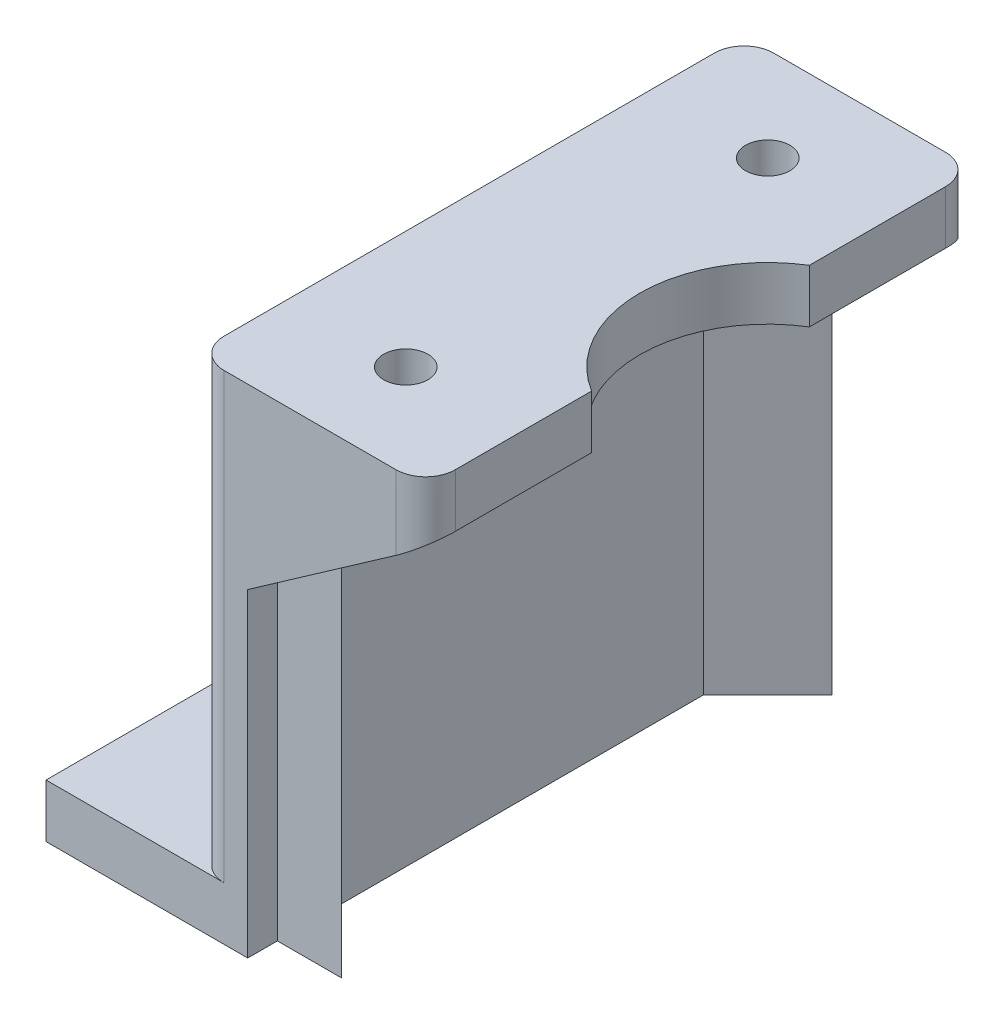
SolidWorks part; units mm, degrees
ref_plane "Front Plane" through (0, 0, 0) normal (0, 0, 1) x (1, 0, 0)
ref_plane "Top Plane" through (0, 0, 0) normal (0, 1, 0) x (1, 0, 0)
ref_plane "Right Plane" through (0, 0, 0) normal (1, 0, 0) x (0, 0, -1)
sketch "Sketch1" plane through (0, 0, 0) normal (0, 0, 1) x (1, 0, 0)
  line L0 (-41.9989, 1.778) -> (-46.5709, 1.778)
  line L1 (-46.5709, 6.35) -> (-46.5709, 44.3509)
  line L2 (-46.5709, 44.3509) -> (-26.7589, 44.3509)
  line L3 (-41.9989, 6.35) -> (-41.9989, 1.778)
  line L4 (-26.7589, 39.7789) -> (-41.9989, 39.7789)
  line L5 (-41.9989, 39.7789) -> (-41.9989, 6.35)
  line L7 (0, 6.35) -> (0, 0)
  line L8 (-26.7589, 44.3509) -> (-26.7589, 39.7789)
  line L9 (-46.5709, 1.778) -> (-59.2709, 1.778)
  line L11 (-46.5709, 6.35) -> (-59.2709, 6.35)
  line L12 (-59.2709, 1.778) -> (-59.2709, 6.35)
  dimension "D1" = 38.0009
  dimension "D2" = 15.24
  dimension "D3" = 4.572
  dimension "D4" = 4.572
  dimension "D5" = 41.9989
  dimension "D7" = 4.572
  dimension "D8" = 12.7
extrude "Boss-Extrude1" add sketch "Sketch1" along normal blind 47.0789 contours L12 L9 L0 L3 L5 L4 L8 L2 L1 L11
ref_plane "Plane1" through (0, 0, 23.5394) normal (0, 0, -1) x (-1, 0, 0)
sketch "Sketch2" plane through (0, 0, 47.0789) normal (0, 0, 1) x (1, 0, 0)
  line L0 (-26.7589, 39.7789) -> (-41.9989, 29.1109)
  line L1 (-41.9989, 39.7789) -> (-41.9989, 1.778) construction
  line L2 (-41.9989, 29.1109) -> (-41.9989, 39.7789)
  line L3 (-41.9989, 39.7789) -> (-26.7589, 39.7789)
extrude "Boss-Extrude2" add sketch "Sketch2" against normal blind 2.54
mirror "Mirror1" about plane through (0, 0, 23.5394) normal (0, 0, -1) of "Boss-Extrude2"
hole_wizard "#6 Clearance Hole1" positions "Sketch3" profile "Sketch4" hole size "#6" standard "ANSI Inch" end condition through all
sketch "Sketch3" plane through (0, 44.3509, 0) normal (0, 1, 0) x (1, 0, 0)
  line L0 (-36.4998, -8.0391) -> (-36.4998, -39.0398)
  line L5 (-46.5709, 0) -> (-46.5709, -47.0789)
  point P0 (-36.4998, -8.0391)
  point P2 (-36.4998, -39.0398)
  point P21 (-36.4998, -23.5394)
  point P22 (-46.5709, -23.5394)
  dimension "D1" = 31.0007
  dimension "D2" = 0
  dimension "D3" = 10.0711
sketch "Sketch4" plane through (-36.4998, 44.3509, 8.0391) normal (1, 0, 0) x (0, 0, 1)
  line L0 (0, 0) -> (0, 42.5729)
  line L1 (0, 42.5729) -> (1.8986, 42.5729)
  line L2 (1.8986, 42.5729) -> (1.8986, 0)
  line L5 (1.8986, 0) -> (0, 0)
  line L11 (0, -6.35) -> (0, 107.95) construction
  dimension "Thru Hole Dia." = 3.7973
  dimension "Thru Hole Depth" = 42.5729
sketch "Sketch5" plane through (0, 44.3509, 0) normal (0, 1, 0) x (1, 0, 0)
  line L0 (-26.7589, -23.5394) -> (-21.0007, -23.5394)
  line L1 (-26.7589, -47.0789) -> (-26.7589, 0) construction
  circle A0 centre (-21.0007, -23.5394) radius 10.9601
  line M7 (-26.7589, -47.0789) -> (-26.7589, 0)
  dimension "D2" = 21.9202
  dimension "D1" = 5.7582
extrude "Cut-Extrude1" cut sketch "Sketch5" against normal through all contours A0 M7
fillet "Fillet1" radius 2.54 4 edges at (-46.5709, 25.3505, 0) (-46.5709, 25.3505, 47.0789) (-26.7589, 42.0649, 47.0789) (-26.7589, 42.0649, 0)
hole_wizard "#6 Clearance Hole2" positions "Sketch6" profile "Sketch7" hole size "#6" standard "ANSI Inch" end condition through all
sketch "Sketch6" plane through (0, 6.35, 0) normal (0, 1, 0) x (1, 0, 0)
  line L0 (-52.9209, -10.8395) -> (-52.9209, -36.2394)
  line L2 (-59.2709, -47.0789) -> (-59.2709, 0) construction
  line L3 (-59.2709, 0) -> (-59.2709, -47.0789)
  point P0 (-52.9209, -10.8395)
  point P2 (-52.9209, -36.2394)
  point P16 (-59.2709, -23.5394)
  point P17 (-52.9209, -23.5394)
  dimension "D1" = 6.35
  dimension "D2" = 25.4
  dimension "D3" = 0
sketch "Sketch7" plane through (-52.9209, 6.35, 10.8395) normal (1, 0, 0) x (0, 0, 1)
  line L0 (0, 0) -> (0, 4.572)
  line L1 (0, 4.572) -> (1.8986, 4.572)
  line L2 (1.8986, 4.572) -> (1.8986, 0)
  line L5 (1.8986, 0) -> (0, 0)
  line L11 (0, -6.35) -> (0, 107.95) construction
  dimension "Thru Hole Dia." = 3.7973
  dimension "Thru Hole Depth" = 4.572
sketch "Sketch8" plane through (0, 39.7789, 0) normal (0, -1, 0) x (1, 0, 0)
  line L0 (-41.9989, 44.5389) -> (-41.9989, 39.0398)
  line L1 (-41.9989, 44.5389) -> (-41.9989, 2.54) construction
  line L2 (-41.9989, 39.0398) -> (-36.4998, 44.5389)
  line L3 (-26.7589, 44.5389) -> (-41.9989, 44.5389) construction
  line L4 (-36.4998, 44.5389) -> (-41.9989, 44.5389)
  line L5 (-41.9989, 2.54) -> (-36.4998, 2.54)
  line L6 (-26.7589, 2.54) -> (-41.9989, 2.54) construction
  line L7 (-36.4998, 2.54) -> (-41.9989, 8.0391)
  line L8 (-41.9989, 8.0391) -> (-41.9989, 2.54)
  dimension "D1" = 5.4991
  dimension "D2" = 5.4991
  dimension "D3" = 5.4991
extrude "Boss-Extrude3" add sketch "Sketch8" along normal blind 38.0009
